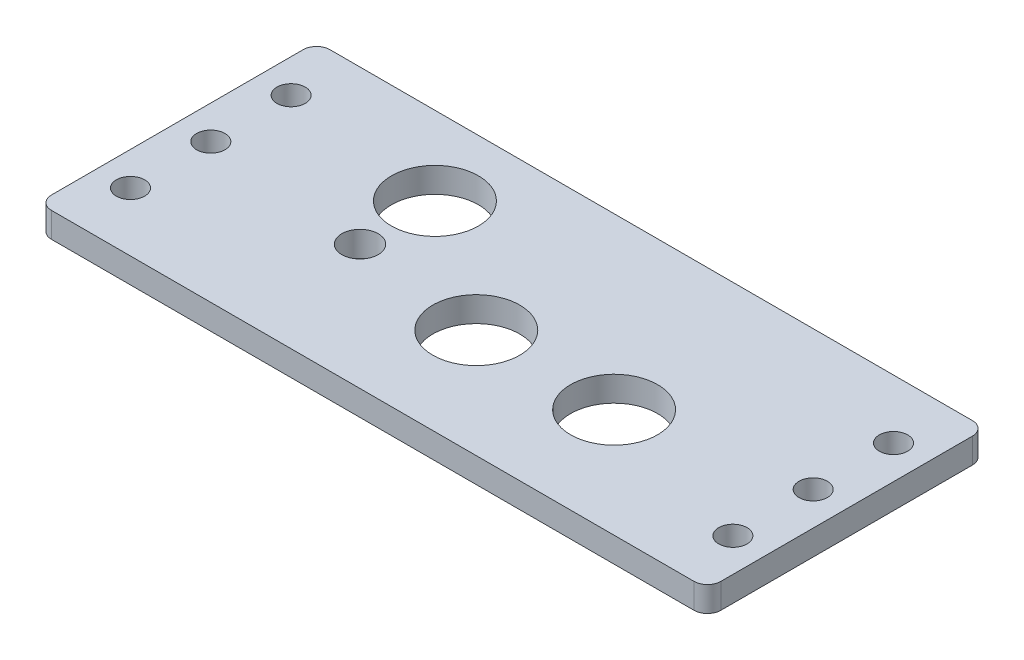
SolidWorks part; units mm, degrees
material "PE High Density Film"
ref_plane "Front Plane" through (0, 0, 0) normal (0, 0, 1) x (1, 0, 0)
ref_plane "Top Plane" through (0, 0, 0) normal (0, 1, 0) x (1, 0, 0)
ref_plane "Right Plane" through (0, 0, 0) normal (1, 0, 0) x (0, 0, -1)
sketch "Sketch1" plane through (0, 0, 0) normal (0, 1, 0) x (1, 0, 0)
  line L1 (-63.5, 26.416) -> (63.5, 26.416)
  line L2 (-63.5, 26.416) -> (-63.5, -26.416)
  line L3 (-63.5, -26.416) -> (63.5, -26.416)
  line L4 (63.5, 26.416) -> (63.5, -26.416)
  line L5 (-63.5, 26.416) -> (63.5, -26.416) construction
  line L6 (-63.5, -26.416) -> (63.5, 26.416) construction
  point P0 (0, 0)
  dimension "D1" = 127
  dimension "D2" = 52.832
extrude "Boss-Extrude1" add sketch "Sketch1" along normal blind 4.7625
fillet "Fillet1" radius 2.54 4 edges at (63.5, 2.3813, 26.416) (63.5, 2.3813, -26.416) (-63.5, 2.3813, -26.416) (-63.5, 2.3813, 26.416)
sketch "Sketch2" plane through (0, 0, 0) normal (0, -1, 0) x (1, 0, 0)
  line L4 (-60.96, 26.416) -> (60.96, 26.416) construction
  circle A0 centre (57.15, -15.24) radius 2.69
  circle A1 centre (57.15, 0) radius 2.69
  circle A2 centre (57.15, 15.24) radius 2.69
  dimension "D1" = 5.38
  dimension "D2" = 11.176
  dimension "D3" = 15.24
  dimension "D4" = 15.24
extrude "Cut-Extrude1" cut sketch "Sketch2" against normal through all
mirror "Mirror1" about plane through (0, 0, 0) normal (1, 0, 0) of "Cut-Extrude1"
sketch "Sketch3" plane through (0, 4.7625, 0) normal (0, 1, 0) x (1, 0, 0)
  circle A0 centre (25.1643, -5.7912) radius 8.25
  circle A1 centre (-0.9857, -5.7912) radius 8.25
extrude "Cut-Extrude2" cut sketch "Sketch3" against normal through all
sketch "Sketch4" plane through (0, 4.7625, 0) normal (0, 1, 0) x (1, 0, 0)
  circle A0 centre (-26.1437, 11.5226) radius 8.255
  circle A1 centre (-26.1437, -2.6959) radius 3.4505
  dimension "D1" = 16.51
extrude "Cut-Extrude3" cut sketch "Sketch4" against normal through all
sketch "Sketch5" plane through (0, 0, 0) normal (0, -1, 0) x (1, 0, 0)
  line L0 (0, -26.416) -> (0, 36.7921) construction
  line L1 (60.96, -26.416) -> (-60.96, -26.416) construction
